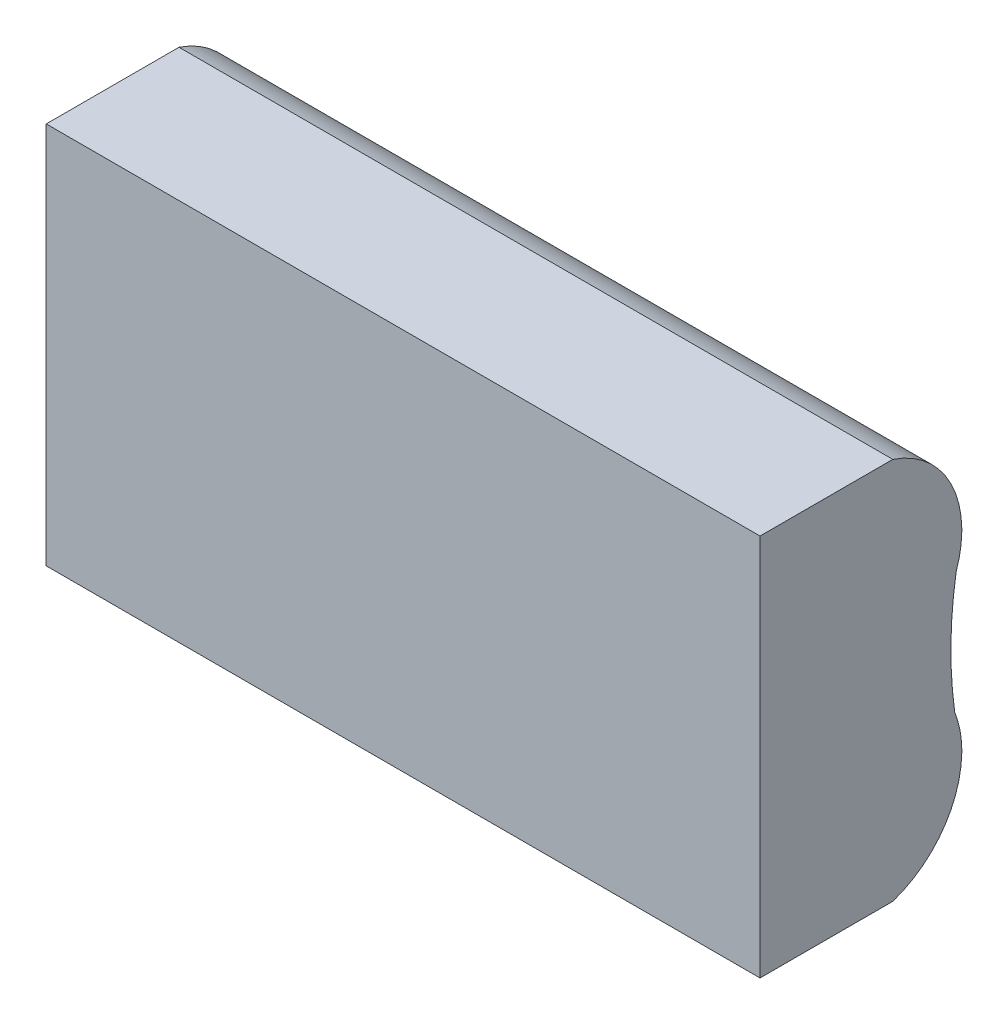
SolidWorks part; units mm, degrees
ref_plane "Alzado" through (0, 0, 0) normal (0, 0, 1) x (1, 0, 0)
ref_plane "Planta" through (0, 0, 0) normal (0, 1, 0) x (1, 0, 0)
ref_plane "Vista lateral" through (0, 0, 0) normal (1, 0, 0) x (0, 0, -1)
sketch "Croquis1" plane through (0, 0, 0) normal (0, 0, 1) x (1, 0, 0)
  line L1 (-34.5, 18.5) -> (34.5, 18.5)
  line L2 (-34.5, 18.5) -> (-34.5, -18.5)
  line L3 (-34.5, -18.5) -> (34.5, -18.5)
  line L4 (34.5, 18.5) -> (34.5, -18.5)
  line L5 (-34.5, 18.5) -> (34.5, -18.5) construction
  line L6 (-34.5, -18.5) -> (34.5, 18.5) construction
  point P0 (0, 0)
  dimension "D1" = 37
  dimension "D2" = 69
extrude "Saliente-Extruir1" add sketch "Croquis1" along normal blind 19.5
ref_plane "Plano1" through (34.5, 0, 0) normal (1, 0, 0) x (0, 0, -1)
sketch "Croquis2" plane through (34.5, 0, 0) normal (1, 0, 0) x (0, 0, -1)
  line L0 (0, 0) -> (-1.0519, 0) construction
  line L1 (-19.5, -18.5) -> (-19.5, 18.5) construction
  line L2 (-19.5, 18.5) -> (-19.4513, 10.2031)
  line L4 (-19.5, 18.5) -> (0, 18.5)
  line L7 (-19.496, -18.5) -> (0, -18.5)
  line L9 (-19.496, 17.5) -> (-17.9135, 14.5779) construction
  line L10 (-19.496, -18.5) -> (-17.6097, -15.0168) construction
  line L11 (0, 18.5) -> (0, -18.5)
  line L12 (-19.498, 9.25) -> (-19.498, -9.25)
  line L13 (0.002, 9.25) -> (0.002, -9.25)
  line L14 (-12.8302, 18.5) -> (-6.6658, 18.5)
  line L15 (-12.8302, -18.5) -> (-6.6658, -18.5)
  line L16 (-18.4481, 0) -> (-19.5, 0) construction
  line L17 (-19.496, -18.5) -> (-19.4746, -9.9255)
  line L18 (-1.8863, -15.0168) -> (0, -18.5) construction
  line L21 (-1.5825, 14.5779) -> (0, 17.5) construction
  arc A0 (-12.8302, 18.5) -> (-18.961, 6.0588) centre (-9.748, 9.25) ccw
  arc A1 (-6.6658, -18.5) -> (-0.6778, -5.673) centre (-9.748, -9.25) ccw
  arc A2 (-18.961, 6.0588) -> (-18.8182, -5.673) centre (-57.8089, -0.2808) cw
  arc A3 (-0.5351, 6.0588) -> (-0.6778, -5.673) centre (37.96, -0.2765) ccw
  arc A5 (-18.8182, -5.673) -> (-12.8302, -18.5) centre (-9.748, -9.25) ccw
  arc A6 (-9.748, 0.5) -> (-10.2817, 0.4854) centre (-9.748, -9.25) ccw
  arc A7 (-0.5351, 6.0588) -> (-6.6658, 18.5) centre (-9.748, 9.25) ccw
  point P10 (-9.748, -0.5)
  dimension "D3" = 19.5
  dimension "D4" = 19.5
  dimension "D1" = 18.5
extrude "Cortar-Extruir3" cut sketch "Croquis2" against normal blind 70 contours A7 L11 L4 | A7 A3 A1 L11 | A1 L7 L11
